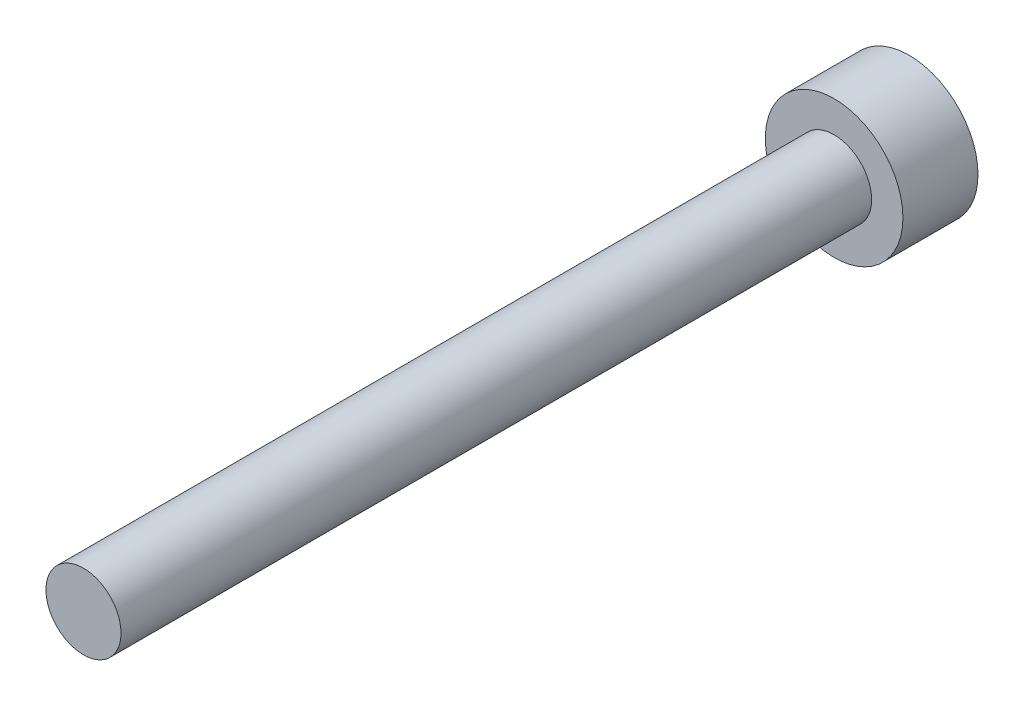
SolidWorks part; units mm, degrees
ref_plane "Front Plane" through (0, 0, 0) normal (0, 0, 1) x (1, 0, 0)
ref_plane "Top Plane" through (0, 0, 0) normal (0, 1, 0) x (1, 0, 0)
ref_plane "Right Plane" through (0, 0, 0) normal (1, 0, 0) x (0, 0, -1)
sketch "S01 - Head" plane through (0, 0, 0) normal (0, 0, 1) x (1, 0, 0)
  circle A0 centre (0, 0) radius 2.75
  dimension "D1" = 5.5
extrude "01 - Head" add sketch "S01 - Head" along normal blind 3 from offset 3
sketch "S02 - Nominal shank" plane through (0, 0, 0) normal (0, 0, 1) x (1, 0, 0)
  circle A0 centre (0, 0) radius 1.5
  dimension "D1" = 3
extrude "02 - Nominal shank" add sketch "S02 - Nominal shank" along normal blind 30
sketch "S03 - Hex key socket" plane through (0, 0, 0) normal (0, 0, 1) x (1, 0, 0)
  line L0 (1.4434, 0) -> (0.7217, 1.25)
  line L1 (0.7217, 1.25) -> (-0.7217, 1.25)
  line L2 (-0.7217, 1.25) -> (-1.4434, 0)
  line L3 (-1.4434, 0) -> (-0.7217, -1.25)
  line L4 (-0.7217, -1.25) -> (0.7217, -1.25)
  line L5 (0.7217, -1.25) -> (1.4434, 0)
  dimension "D1" = 0.7217
  dimension "D2" = 1.4434
  dimension "D3" = 0.7217
  dimension "D4" = 1.4434
  dimension "D5" = 1.25
  dimension "D6" = 1.25
extrude "03 - Hex key socket" cut sketch "S03 - Hex key socket" along normal blind 1.75 from offset 3.1
